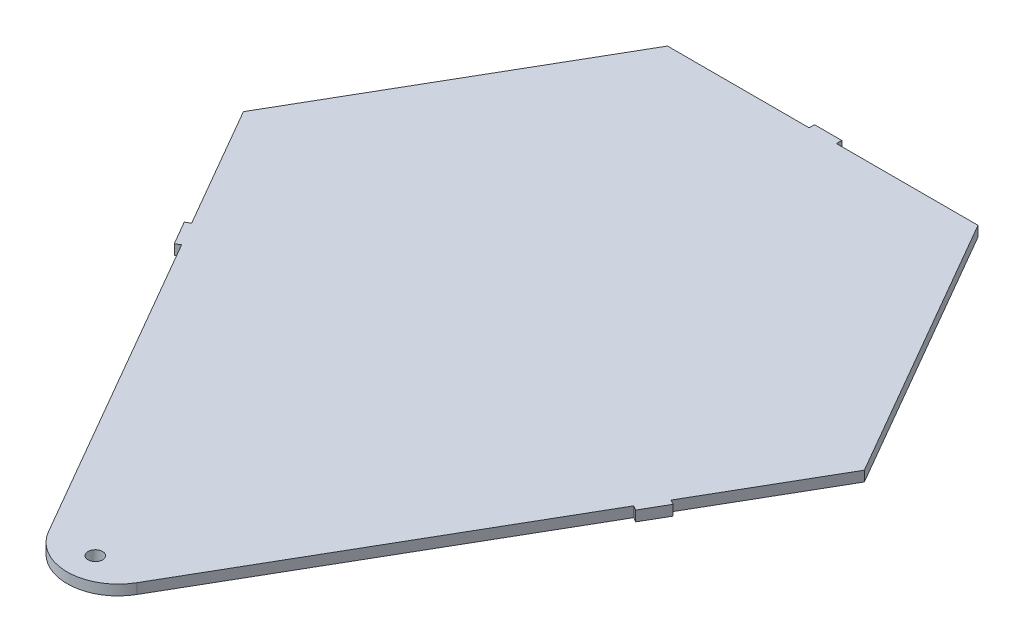
SolidWorks part; units mm, degrees
ref_plane "Front Plane" through (0, 0, 0) normal (0, 0, 1) x (1, 0, 0)
ref_plane "Top Plane" through (0, 0, 0) normal (0, 1, 0) x (1, 0, 0)
ref_plane "Right Plane" through (0, 0, 0) normal (1, 0, 0) x (0, 0, -1)
sketch "Sketch1" plane through (0, 0, 0) normal (0, 1, 0) x (1, 0, 0)
  line L0 (-7.5, 147.6573) -> (-85.25, 147.6573)
  line L1 (85.25, -147.6573) -> (124.1505, -80.2796)
  line L2 (170.5, 0) -> (85.25, 147.6573)
  line L3 (85.25, 147.6573) -> (7.5, 147.6573)
  line L4 (-85.25, 147.6573) -> (-170.5, 0)
  line L5 (-170.5, 0) -> (-131.6505, -67.2893)
  line L8 (-7.5, 147.6573) -> (-7.5, 150.6073)
  line L9 (-7.5, 150.6073) -> (7.5, 150.6073)
  line L10 (7.5, 147.6573) -> (7.5, 150.6073)
  line L19 (-131.6505, -67.2893) -> (-134.2053, -68.7643)
  line L20 (-134.2053, -68.7643) -> (-126.7053, -81.7546)
  line L21 (-126.7053, -81.7546) -> (-124.1505, -80.2796)
  line L22 (-124.1505, -80.2796) -> (-85.25, -147.6573)
  line L23 (124.1505, -80.2796) -> (126.7053, -81.7546)
  line L24 (126.7053, -81.7546) -> (134.2053, -68.7643)
  line L25 (134.2053, -68.7643) -> (131.6505, -67.2893)
  line L26 (131.6505, -67.2893) -> (170.5, 0)
  line L27 (-85.25, -147.6573) -> (85.25, -147.6573) [skipped]
  line L28 (-85.25, -147.6573) -> (0, -295.3147)
  line L29 (85.25, -147.6573) -> (0, -295.3147)
  circle A0 centre (0, 0) radius 147.6573 construction
  circle A1 centre (0, -227.3147) radius 4
  point P20 (130.4553, -75.2594)
  point P21 (0, 150.6073)
  point P24 (-130.4553, -75.2594)
  point P27 (-7.5, -227.729)
  point P30 (0, 0)
  dimension "D12" = 8
  dimension "D1" = 15
  dimension "D2" = 85.25
  dimension "D3" = 170.5
  dimension "D4" = 2.95
  dimension "D5" = 15
  dimension "D6" = 2.95
  dimension "D7" = 85.25
  dimension "D8" = 2.95
  dimension "D9" = 15
  dimension "D10" = 85.25
  dimension "D11" = 68
extrude "Boss-Extrude1" add sketch "Sketch1" along normal blind 5.63 contours L4 L5 L19 L20 L21 L22 L28 L29 L1 L23 L24 L25 L26 L2 L3 L10 L9 L8 L0
fillet "Fillet1" radius 28 1 edges at (0, 2.815, 295.3147)
sketch "Sketch2" plane through (0, 5.63, 0) normal (0, 1, 0) x (1, 0, 0)
  circle A0 centre (0, -251.8348) radius 4
  point P2 (0, -242.5927)
  point P3 (0, -251.8348)
extrude "Cut-Extrude4" cut sketch "Sketch2" against normal blind 10
equation "\"Side\"= 170.5"
equation "\"thick acrylic\"= 5.63"
equation "\"connect width\"= 15"
equation "\"thin acrylic\"= 2.95"
equation "\"D1@Sketch1\"=\"connect width\""
equation "\"D2@Sketch1\"=\"Side\"/2"
equation "\"D3@Sketch1\"=\"Side\""
equation "\"D4@Sketch1\"=\"thin acrylic\""
equation "\"D5@Sketch1\"=\"connect width\""
equation "\"D6@Sketch1\"=\"thin acrylic\""
equation "\"D7@Sketch1\"=\"Side\"/2"
equation "\"D8@Sketch1\"=\"thin acrylic\""
equation "\"D9@Sketch1\"=\"connect width\""
equation "\"D10@Sketch1\"=\"Side\"/2"
equation "\"D1@Boss-Extrude1\"=\"thick acrylic\""
